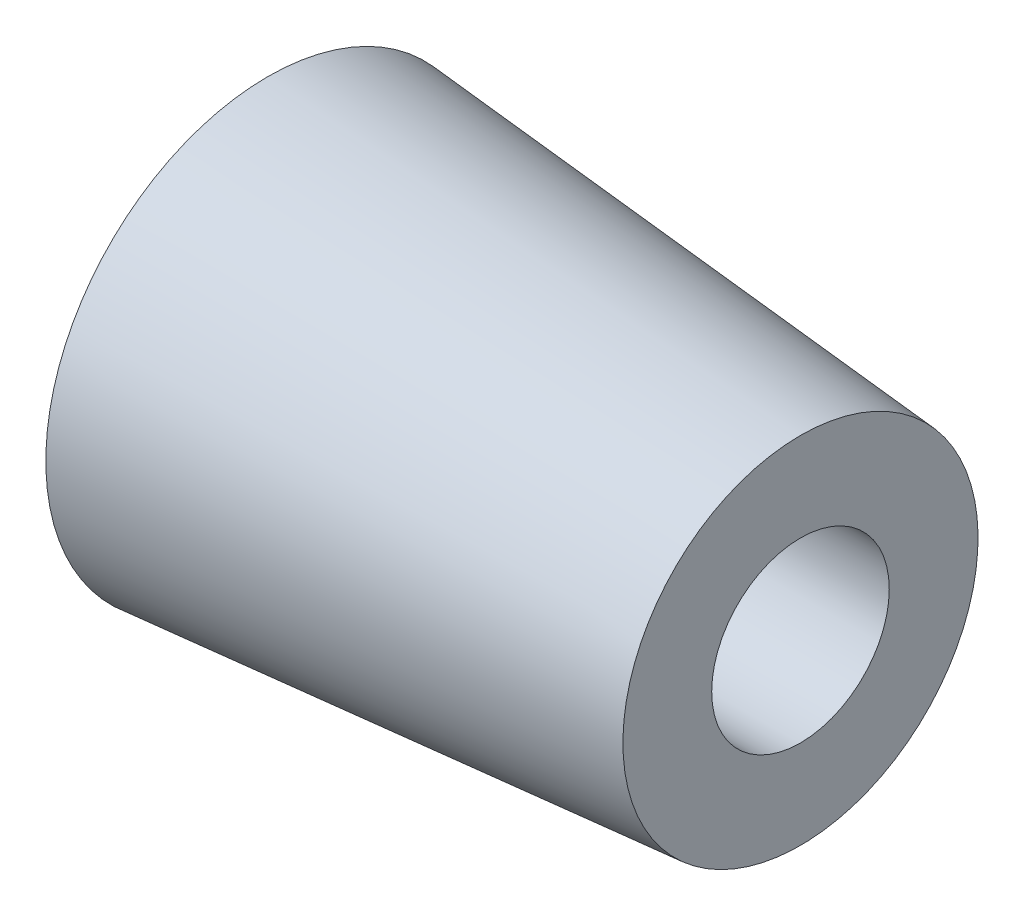
SolidWorks part; units mm, degrees
ref_plane "Front Plane" through (0, 0, 0) normal (0, 0, 1) x (1, 0, 0)
ref_plane "Top Plane" through (0, 0, 0) normal (0, 1, 0) x (1, 0, 0)
ref_plane "Right Plane" through (0, 0, 0) normal (1, 0, 0) x (0, 0, -1)
sketch "Sketch1" plane through (0, 0, 0) normal (0, 0, 1) x (1, 0, 0)
  line L0 (0, 0) -> (0, 2.5)
  line L1 (0, 2.5) -> (6, 2)
  line L2 (6, 2) -> (6, 1)
  line L3 (6, 1) -> (2.75, 1)
  line L4 (2.75, 1) -> (2.75, 0)
  line L5 (2.75, 0) -> (0, 0)
  dimension "D1" = 2.5
  dimension "D2" = 6
  dimension "D3" = 3.25
  dimension "D4" = 1
  dimension "D5" = 1
revolve "Revolve1" add sketch "Sketch1" angle 360 about L5
sketch "Sketch2" plane through (0, 0, 0) normal (0, 1, 0) x (1, 0, 0)
  line L0 (6, -2) -> (6, 2) construction
  circle A0 centre (4, 0) radius 0.5
  dimension "D1" = 1
  dimension "D2" = 2
extrude "Cut-Extrude1" cut sketch "Sketch2" against normal up to next
